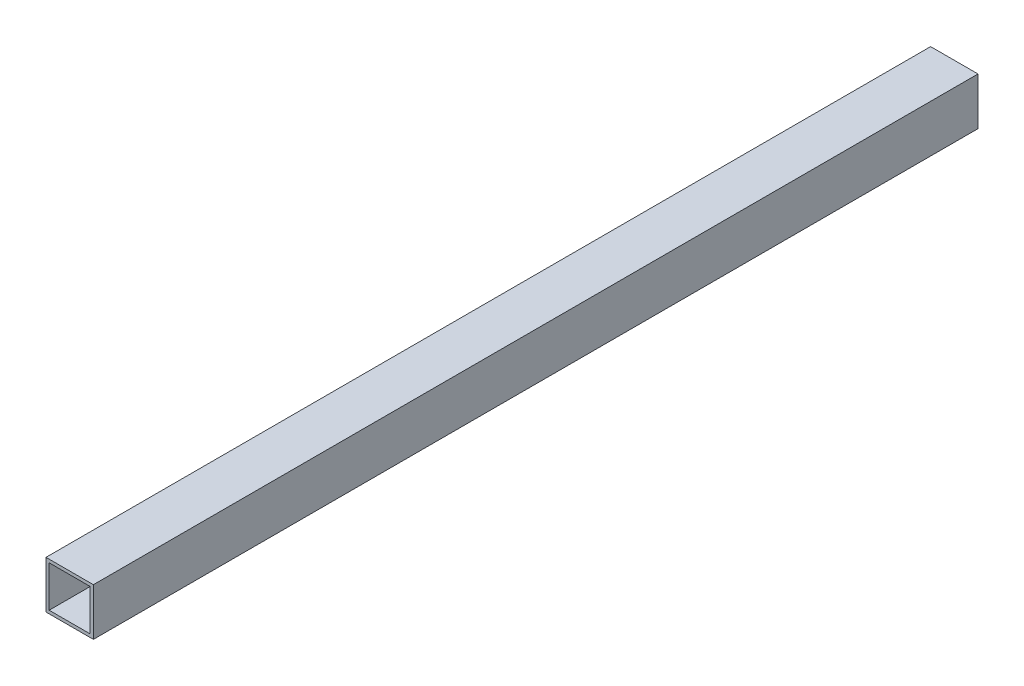
SolidWorks part; units mm, degrees
material "1060 Alloy"
ref_plane "Front Plane" through (0, 0, 0) normal (0, 0, 1) x (1, 0, 0)
ref_plane "Top Plane" through (0, 0, 0) normal (0, 1, 0) x (1, 0, 0)
ref_plane "Right Plane" through (0, 0, 0) normal (1, 0, 0) x (0, 0, -1)
sketch "Sketch1" plane through (0, 0, 0) normal (0, 0, 1) x (1, 0, 0)
  line L0 (-7.5, 7.5) -> (7.5, 7.5)
  line L1 (-6.5, 6.5) -> (6.5, 6.5)
  line L2 (-6.5, 6.5) -> (-6.5, -6.5)
  line L3 (-6.5, -6.5) -> (6.5, -6.5)
  line L4 (6.5, 6.5) -> (6.5, -6.5)
  line L5 (-6.5, 6.5) -> (6.5, -6.5) construction
  line L6 (-6.5, -6.5) -> (6.5, 6.5) construction
  line L7 (7.5, 7.5) -> (7.5, -7.5)
  line L8 (-7.5, -7.5) -> (7.5, -7.5)
  line L9 (-7.5, 7.5) -> (-7.5, -7.5)
  point P0 (0, 0)
  dimension "D2" = 15
  dimension "D3" = 15
  dimension "D1" = 1
extrude "Boss-Extrude1" add sketch "Sketch1" along normal blind 280
